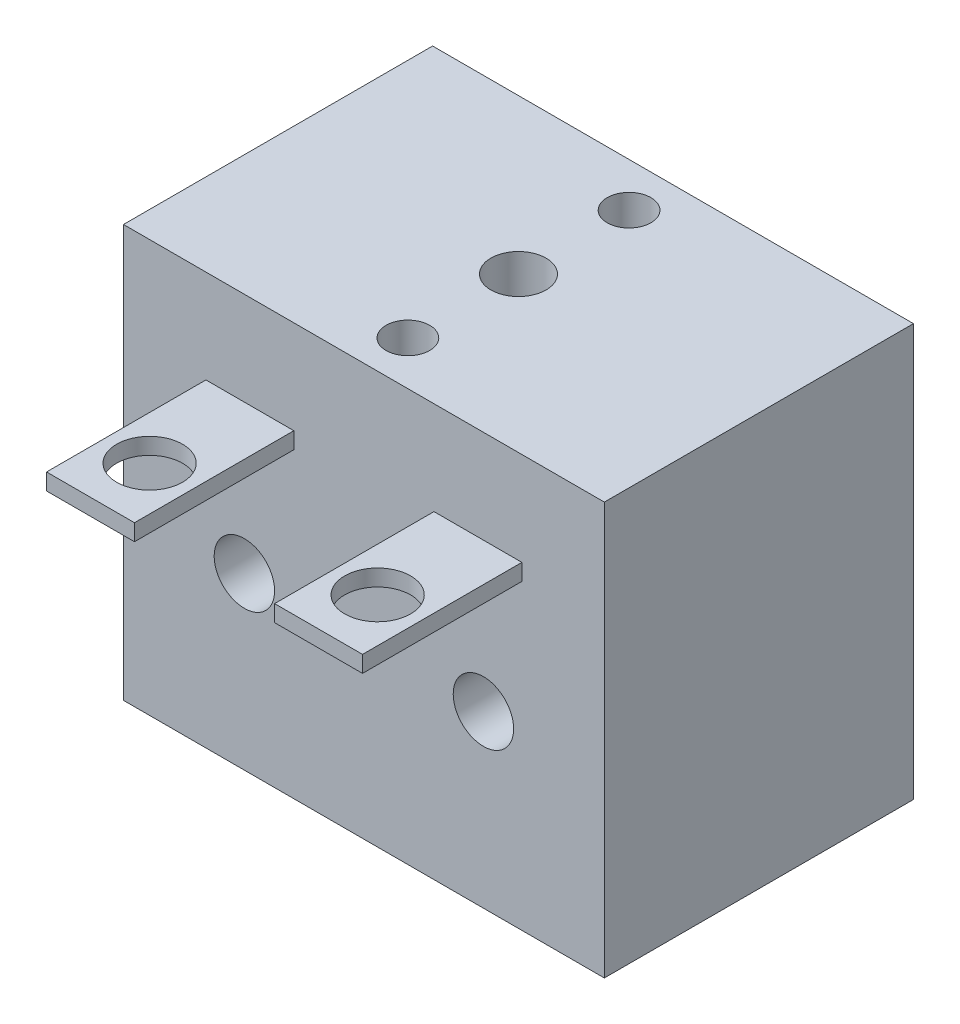
SolidWorks part; units mm, degrees
material "Nylon 6/10"
ref_plane "Front Plane" through (0, 0, 0) normal (0, 0, 1) x (1, 0, 0)
ref_plane "Top Plane" through (0, 0, 0) normal (0, 1, 0) x (1, 0, 0)
ref_plane "Right Plane" through (0, 0, 0) normal (1, 0, 0) x (0, 0, -1)
sketch "Sketch1" plane through (0, 0, 0) normal (0, 1, 0) x (1, 0, 0)
  line L1 (0, 0) -> (44.45, 0)
  line L2 (0, 0) -> (0, 28.575)
  line L3 (0, 28.575) -> (44.45, 28.575)
  line L4 (44.45, 0) -> (44.45, 28.575)
  dimension "D1" = 28.575
  dimension "D2" = 44.45
extrude "Extrude1" add sketch "Sketch1" along normal blind 38.1
sketch "Sketch2" plane through (0, 38.1, 0) normal (0, 1, 0) x (-1, 0, 0)
  line L0 (-44.45, 0) -> (-44.45, -28.575) construction
  line L1 (0, 0) -> (-44.45, 0) construction
  line L2 (-44.45, -28.575) -> (0, -28.575) construction
  line L3 (0, -28.575) -> (0, 0) construction
  circle A0 centre (-22.225, -14.2875) radius 2.5527
  circle A1 centre (-22.225, -24.511) radius 2.0193
  circle A2 centre (-22.225, -4.064) radius 2.0193
  dimension "D3" = 5.1054
  dimension "D6" = 4.0386
  dimension "D7" = 4.0386
  dimension "D1" = 22.225
  dimension "D2" = 14.2875
  dimension "D4" = 4.064
  dimension "D5" = 4.064
  dimension "D8" = 22.225
  dimension "D9" = 22.225
extrude "Cut-Extrude1" cut sketch "Sketch2" against normal through all
sketch "Sketch3" plane through (0, 0, -28.575) normal (0, 0, -1) x (-1, 0, 0)
  line L0 (-44.45, 38.1) -> (-44.45, 0) construction
  line L1 (0, 38.1) -> (0, 0) construction
  line L2 (-44.45, 38.1) -> (0, 38.1) construction
  circle A0 centre (-33.274, 15.748) radius 2.794
  circle A1 centre (-11.176, 15.748) radius 2.794
  dimension "D1" = 5.588
  dimension "D2" = 5.588
  dimension "D3" = 11.176
  dimension "D4" = 11.176
  dimension "D5" = 22.352
  dimension "D6" = 22.352
extrude "Cut-Extrude2" cut sketch "Sketch3" against normal through all
sketch "Sketch4" plane through (0, 0, 0) normal (0, 0, 1) x (1, 0, 0)
  line L0 (0, 38.1) -> (0, 0) construction
  line L1 (7.62, 29.464) -> (15.748, 29.464)
  line L2 (7.62, 29.464) -> (7.62, 27.94)
  line L3 (7.62, 27.94) -> (15.748, 27.94)
  line L4 (15.748, 29.464) -> (15.748, 27.94)
  line L5 (28.702, 29.464) -> (36.83, 29.464)
  line L6 (28.702, 29.464) -> (28.702, 27.94)
  line L7 (28.702, 27.94) -> (36.83, 27.94)
  line L8 (36.83, 29.464) -> (36.83, 27.94)
  line L9 (0, 38.1) -> (44.45, 38.1) construction
  line L10 (44.45, 38.1) -> (44.45, 0) construction
  dimension "D1" = 1.524
  dimension "D2" = 8.128
  dimension "D3" = 7.62
  dimension "D4" = 8.636
  dimension "D5" = 8.128
  dimension "D6" = 7.62
extrude "Extrude2" add sketch "Sketch4" along normal blind 14.732
sketch "Sketch5" plane through (0, 29.464, 0) normal (0, 1, 0) x (-1, 0, 0)
  line L0 (-44.45, -28.575) -> (0, -28.575) construction
  line L1 (-36.83, 14.732) -> (-36.83, 0) construction
  line L2 (-7.62, 14.732) -> (-7.62, 0) construction
  circle A0 centre (-11.684, 9.271) radius 3.048
  circle A1 centre (-32.766, 9.271) radius 3.048
  dimension "D2" = 6.096
  dimension "D6" = 6.096
  dimension "D1" = 37.846
  dimension "D3" = 4.064
  dimension "D4" = 37.846
  dimension "D5" = 4.064
extrude "Cut-Extrude3" cut sketch "Sketch5" against normal through all
